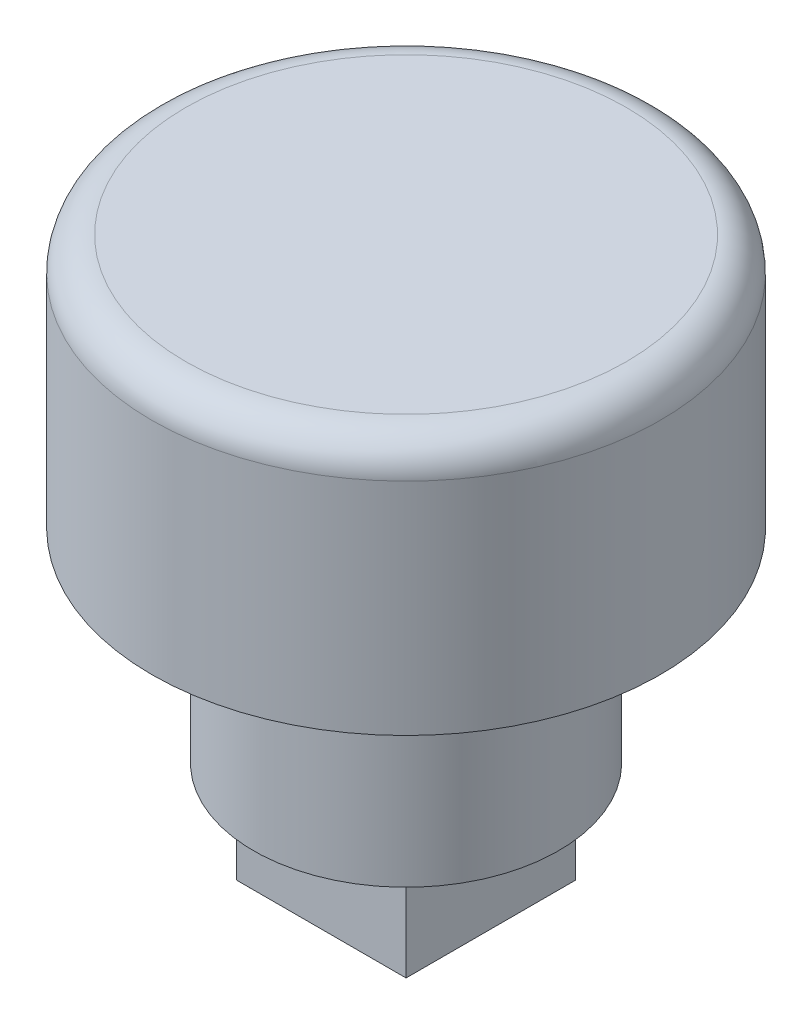
SolidWorks part; units mm, degrees
ref_plane "Front Plane" through (0, 0, 0) normal (0, 0, 1) x (1, 0, 0)
ref_plane "Top Plane" through (0, 0, 0) normal (0, 1, 0) x (1, 0, 0)
ref_plane "Right Plane" through (0, 0, 0) normal (1, 0, 0) x (0, 0, -1)
sketch "Sketch1" plane through (0, 0, 0) normal (0, 1, 0) x (1, 0, 0)
  circle A0 centre (0, 0) radius 7.5
  dimension "D1" = 15
extrude "Boss-Extrude1" add sketch "Sketch1" along normal blind 7.5
fillet "Fillet1" radius 1 1 edges at (0, 7.5, 7.5)
sketch "Sketch2" plane through (0, 0, 0) normal (0, -1, 0) x (-1, 0, 0)
  circle A0 centre (0, 0) radius 4.5
  dimension "D1" = 9
extrude "Boss-Extrude2" add sketch "Sketch2" along normal blind 6
sketch "Sketch3" plane through (0, -6, 0) normal (0, -1, 0) x (-1, 0, 0)
  line L1 (-2.5, 2.5) -> (2.5, 2.5)
  line L2 (-2.5, 2.5) -> (-2.5, -2.5)
  line L3 (-2.5, -2.5) -> (2.5, -2.5)
  line L4 (2.5, 2.5) -> (2.5, -2.5)
  line L5 (-2.5, 2.5) -> (2.5, -2.5) construction
  line L6 (-2.5, -2.5) -> (2.5, 2.5) construction
  point P0 (0, 0)
  dimension "D1" = 5
  dimension "D2" = 5
extrude "Boss-Extrude3" add sketch "Sketch3" along normal blind 3
